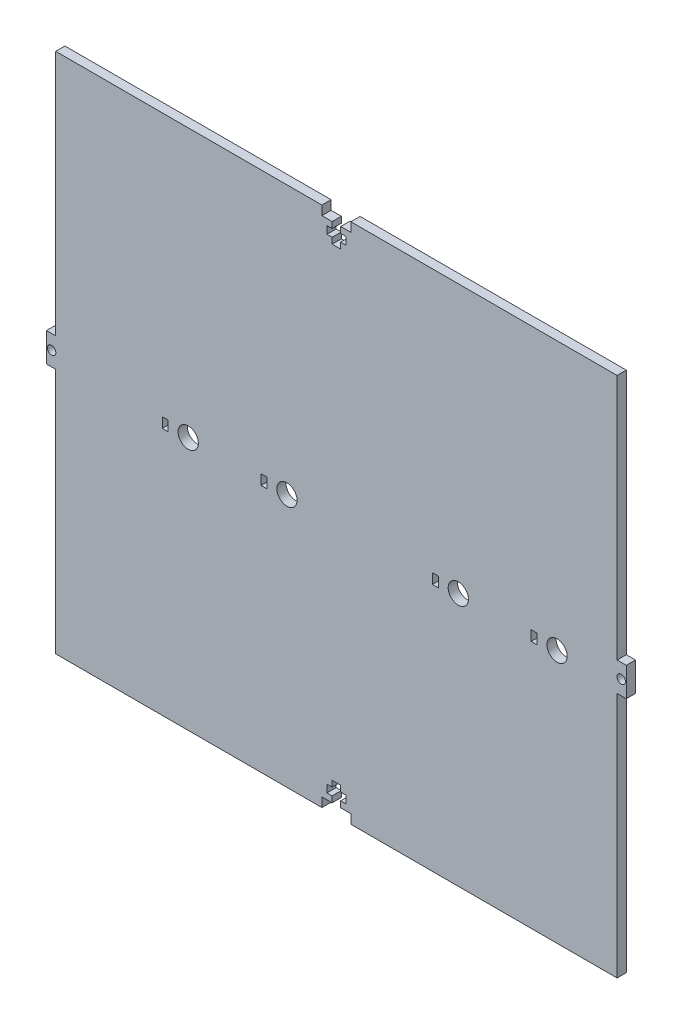
SolidWorks part; units mm, degrees
ref_plane "Front Plane" through (0, 0, 0) normal (0, 0, 1) x (1, 0, 0)
ref_plane "Top Plane" through (0, 0, 0) normal (0, 1, 0) x (1, 0, 0)
ref_plane "Right Plane" through (0, 0, 0) normal (1, 0, 0) x (0, 0, -1)
sketch "Sketch2" plane through (0, 0, 0) normal (0, 0, 1) x (1, 0, 0)
  line L1 (-96.82, -90) -> (96.82, -90)
  line L2 (-96.82, -90) -> (-96.82, 90)
  line L3 (-96.82, 90) -> (96.82, 90)
  line L4 (96.82, -90) -> (96.82, 90)
  line L5 (-96.82, -90) -> (96.82, 90) construction
  line L6 (-96.82, 90) -> (96.82, -90) construction
  point P0 (0, 0)
  dimension "D1" = 180
  dimension "D2" = 193.64
extrude "Boss-Extrude1" add sketch "Sketch2" along normal blind 3.18
sketch "Sketch3" plane through (0, 0, 3.18) normal (0, 0, 1) x (1, 0, 0)
  line L0 (96.82, 90) -> (-96.82, 90) construction
  line L1 (-5, 90) -> (5, 90)
  line L2 (-5, 90) -> (-5, 86.82)
  line L3 (-5, 86.82) -> (-1.47, 86.82)
  line L4 (5, 90) -> (5, 86.82)
  line L5 (0, 90) -> (0, 25.4128) construction
  line L6 (1.47, 82.14) -> (3.25, 82.14)
  line L8 (-1.47, 86.82) -> (-1.47, 84.74)
  line L9 (-1.47, 80.07) -> (1.47, 80.07)
  line L10 (1.47, 86.82) -> (1.47, 84.74)
  line L11 (-3.25, 84.74) -> (-1.47, 84.74)
  line L12 (-3.25, 84.74) -> (-3.25, 82.14)
  line L13 (-3.25, 82.14) -> (-1.47, 82.14)
  line L14 (3.25, 84.74) -> (3.25, 82.14)
  line L15 (-1.47, 82.14) -> (-1.47, 80.07)
  line L16 (1.47, 84.74) -> (3.25, 84.74)
  line L17 (1.47, 86.82) -> (5, 86.82)
  line L18 (1.47, 82.14) -> (1.47, 80.07)
  line L19 (-96.82, 0) -> (96.82, 0) construction
  line L20 (-96.82, 90) -> (-96.82, -90) construction
  line L21 (96.82, -90) -> (96.82, 90) construction
  line L22 (1.47, -86.82) -> (5, -86.82)
  line L23 (5, -90) -> (5, -86.82)
  line L24 (-5, -90) -> (5, -90)
  line L25 (-5, -90) -> (-5, -86.82)
  line L26 (-5, -86.82) -> (-1.47, -86.82)
  line L27 (-1.47, -86.82) -> (-1.47, -84.74)
  line L28 (-3.25, -84.74) -> (-1.47, -84.74)
  line L29 (-3.25, -84.74) -> (-3.25, -82.14)
  line L30 (-3.25, -82.14) -> (-1.47, -82.14)
  line L31 (-1.47, -82.14) -> (-1.47, -80.07)
  line L32 (-1.47, -80.07) -> (1.47, -80.07)
  line L33 (1.47, -82.14) -> (1.47, -80.07)
  line L34 (1.47, -82.14) -> (3.25, -82.14)
  line L35 (3.25, -84.74) -> (3.25, -82.14)
  line L36 (1.47, -84.74) -> (3.25, -84.74)
  line L37 (1.47, -86.82) -> (1.47, -84.74)
  dimension "D1" = 3.18
  dimension "D2" = 10
  dimension "D3" = 2.94
  dimension "D4" = 2.6
  dimension "D5" = 6.75
  dimension "D6" = 6.5
  dimension "D7" = 2.08
extrude "Cut-Extrude1" cut sketch "Sketch3" against normal through all
sketch "Sketch4" plane through (-96.82, 0, 0) normal (-1, 0, 0) x (0, 0, 1)
  line L0 (0, 90) -> (0, -90) construction
  line L1 (0, -5) -> (3.18, -5)
  line L2 (0, -5) -> (0, 5)
  line L3 (0, 5) -> (3.18, 5)
  line L4 (3.18, -5) -> (3.18, 5)
  line L5 (3.18, 90) -> (3.18, -90) construction
  line L6 (0, 0) -> (19.9881, 0) construction
  dimension "D1" = 10
extrude "Boss-Extrude2" add sketch "Sketch4" along normal blind 3.18
sketch "Sketch6" plane through (0, 0, 3.18) normal (0, 0, 1) x (1, 0, 0)
  line L0 (-100, 0) -> (0, 0) construction
  line L1 (-100, -5) -> (-100, 5) construction
  circle A1 centre (-98.25, 0) radius 1.47
  dimension "D1" = 2.94
  dimension "D2" = 1.75
extrude "Cut-Extrude2" cut sketch "Sketch6" against normal through all
mirror "Mirror1" about plane through (0, 0, 0) normal (1, 0, 0) of "Boss-Extrude2"
mirror "Mirror2" about plane through (0, 0, 0) normal (1, 0, 0) of "Cut-Extrude2"
sketch "Sketch7" plane through (0, 0, 3.18) normal (0, 0, 1) x (1, 0, 0)
  line L0 (0, 0) -> (0, 70.8886) construction
  circle A0 centre (-51.1197, -2.5204) radius 3.5
  circle A1 centre (-17.0513, -2.5204) radius 3.5
  circle A2 centre (42.0525, -2.5204) radius 3.5
  circle A3 centre (76.1208, -2.5204) radius 3.5
  dimension "D1" = 7
  dimension "D2" = 7
  dimension "D3" = 7
  dimension "D4" = 7
extrude "Cut-Extrude3" cut sketch "Sketch7" against normal through all
sketch "Sketch9" plane through (0, 0, 0) normal (0, 0, -1) x (-1, 0, 0)
  line L0 (59.353, -3.7704) -> (58.7272, -3.7704) construction
  line L1 (58.0272, -0.7704) -> (60.0514, -0.7704)
  line L2 (58.0272, -0.7704) -> (58.0272, -4.2704)
  line L3 (58.0272, -4.2704) -> (60.0514, -4.2704)
  line L4 (60.0514, -0.7704) -> (60.0514, -4.2704)
  line L5 (59.353, -1.2704) -> (58.7272, -1.2704) construction
  line L6 (58.5272, -3.5704) -> (58.5272, -1.4704) construction
  line L8 (24.4589, -3.5704) -> (24.4589, -1.4704) construction
  line L9 (23.9589, -0.7704) -> (25.983, -0.7704)
  line L10 (23.9589, -0.7704) -> (23.9589, -4.2704)
  line L11 (23.9589, -4.2704) -> (25.983, -4.2704)
  line L12 (25.983, -0.7704) -> (25.983, -4.2704)
  line L13 (25.2846, -3.7704) -> (24.6589, -3.7704) construction
  line L14 (25.2846, -1.2704) -> (24.6589, -1.2704) construction
  line L15 (-34.6449, -3.5704) -> (-34.6449, -1.4704) construction
  line L16 (-35.1449, -0.7704) -> (-33.1208, -0.7704)
  line L17 (-35.1449, -0.7704) -> (-35.1449, -4.2704)
  line L18 (-35.1449, -4.2704) -> (-33.1208, -4.2704)
  line L19 (-33.1208, -0.7704) -> (-33.1208, -4.2704)
  line L20 (-33.8192, -1.2704) -> (-34.4449, -1.2704) construction
  line L21 (-33.8192, -3.7704) -> (-34.4449, -3.7704) construction
  line L22 (-68.7132, -3.5704) -> (-68.7132, -1.4704) construction
  line L23 (-69.2132, -0.7704) -> (-67.1891, -0.7704)
  line L24 (-69.2132, -0.7704) -> (-69.2132, -4.2704)
  line L25 (-69.2132, -4.2704) -> (-67.1891, -4.2704)
  line L26 (-67.1891, -0.7704) -> (-67.1891, -4.2704)
  line L27 (-67.8875, -1.2704) -> (-68.5132, -1.2704) construction
  line L28 (-67.8875, -3.7704) -> (-68.5132, -3.7704) construction
  point P44 (-68.2004, -3.7704)
  dimension "D1" = 0.5
  dimension "D2" = 0.5
  dimension "D3" = 0.5
  dimension "D4" = 0.5
  dimension "D5" = 0.5
  dimension "D6" = 0.5
  dimension "D7" = 0.5
  dimension "D8" = 0.5
  dimension "D9" = 0.5
  dimension "D10" = 0.5
  dimension "D11" = 0.5
  dimension "D12" = 0.5
  dimension "D13" = 0.5
  dimension "D14" = 0.5
  dimension "D15" = 0.5
  dimension "D16" = 0.5
extrude "Cut-Extrude4" cut sketch "Sketch9" against normal through all
